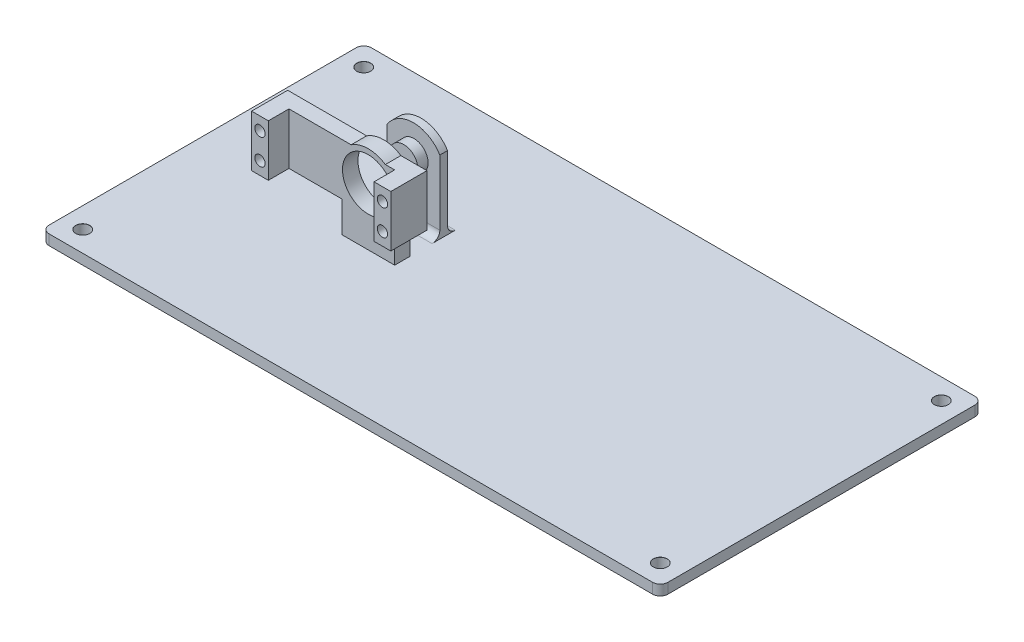
SolidWorks part; units mm, degrees
ref_plane "前视基准面" through (0, 0, 0) normal (0, 0, 1) x (1, 0, 0)
ref_plane "上视基准面" through (0, 0, 0) normal (0, 1, 0) x (1, 0, 0)
ref_plane "右视基准面" through (0, 0, 0) normal (1, 0, 0) x (0, 0, -1)
other "Configuration Table"
sketch "草图1" plane through (0, 0, 0) normal (0, 1, 0) x (1, 0, 0)
  line L1 (-120, -62.5) -> (120, -62.5)
  line L2 (-120, -62.5) -> (-120, 62.5)
  line L3 (-120, 62.5) -> (120, 62.5)
  line L4 (120, -62.5) -> (120, 62.5)
  line L5 (-120, -62.5) -> (120, 62.5) construction
  line L6 (-120, 62.5) -> (120, -62.5) construction
  point P0 (0, 0)
  dimension "D1" = 240
  dimension "D2" = 125
extrude "凸台-拉伸1" add sketch "草图1" along normal blind 4
sketch "草图2" plane through (0, 4, 0) normal (0, 1, 0) x (1, 0, 0)
  line L0 (-120, 0) -> (120, 0) construction
  line L1 (-120, 62.5) -> (-120, -62.5) construction
  line L2 (120, -62.5) -> (120, 62.5) construction
  line L3 (0, 62.5) -> (0, -62.5) construction
  line L4 (120, 62.5) -> (-120, 62.5) construction
  line L5 (-120, -62.5) -> (120, -62.5) construction
  point P12 (-112, 54.5)
  point P13 (-112, -54.5)
  point P14 (112, -54.5)
  point P15 (112, 54.5)
  dimension "D1" = 8
  dimension "D2" = 8
hole_wizard "Ø5.4 (5.4) 直径孔1" positions "草图2" profile "草图3" hole size "Ø5.4" standard "GB" end condition through all
sketch "草图3" plane through (112, 4, -54.5) normal (1, 0, 0) x (0, 0, 1)
  line L0 (0, 0) -> (0, 4)
  line L1 (0, 4) -> (2.7, 4)
  line L2 (2.7, 4) -> (2.7, 0.025)
  line L3 (2.7, 0.025) -> (2.725, 0)
  line L5 (2.725, 0) -> (0, 0)
  line L6 (-2.7, 0.025) -> (-2.725, 0) construction
  line L11 (0, -6.35) -> (0, 107.95) construction
  dimension "通孔孔直径" = 5.4
  dimension "通孔孔深度" = 4
  dimension "近端锥形沉头孔直径" = 5.45
  dimension "近端锥形沉头孔角度" = 90
fillet "圆角1" radius 3 4 edges at (120, 2, 62.5) (120, 2, -62.5) (-120, 2, 62.5) (-120, 2, -62.5)
sketch "草图5" plane through (0, 0, 0) normal (0, 0, 1) x (1, 0, 0)
  line L0 (0, 0) -> (0, 4) construction
  line L1 (-117, 4) -> (117, 4) construction
  line L2 (-60, 0) -> (-60, 4) construction
  line L3 (-117, 0) -> (117, 0) construction
  line L4 (-60, 4) -> (-39.5, 4)
  line L5 (-33, 16) -> (-33, 36)
  line L6 (-33, 36) -> (-43.1168, 36)
  line L8 (-87, 16) -> (-87, 36)
  line L9 (-60, 4) -> (-60, 36) construction
  line L10 (-60, 16) -> (-87, 16)
  line L12 (-49.75, 4) -> (-49.75, 14) construction
  line L13 (-33, 16) -> (-39.5, 16)
  line L14 (-33, 26) -> (-87, 26) construction
  line L15 (-39.5, 16) -> (-39.5, 4)
  line L16 (-49.75, 16) -> (-49.75, 36) construction
  line L17 (-56.3832, 36) -> (-87, 36)
  line L18 (-60, 16) -> (-60, 4)
  arc A1 (-43.1168, 36) -> (-56.3832, 36) centre (-49.75, 26) ccw
  circle A2 centre (-49.75, 26) radius 10
  point P13 (-60, 36)
  dimension "D1" = 60
  dimension "D5" = 20
extrude "凸台-拉伸2" add sketch "草图5" along normal blind 6
sketch "草图6" plane through (0, 0, 0) normal (0, 0, -1) x (-1, 0, 0)
  line L0 (39.5, 4) -> (60, 4)
  line L5 (60, 4) -> (60, 32.24)
  line L9 (39.5, 32.24) -> (39.5, 4)
  line L10 (39.5, 16) -> (60, 16) construction
  line L11 (49.75, 16) -> (49.75, 36) construction
  line L12 (49.75, 26) -> (39.5, 26) construction
  line L13 (39.5, 26) -> (60, 26) construction
  arc A1 (60, 32.24) -> (39.5, 32.24) centre (49.75, 26) ccw
  arc A2 (56.3832, 36) -> (43.1168, 36) centre (49.75, 26) ccw construction
  point P5 (39.5, 32.24)
  point P21 (43.1168, 36)
  point P22 (56.3832, 36)
  point P24 (60, 32.24)
extrude "凸台-拉伸3" add sketch "草图6" along normal blind 3 from offset 11.5
fillet "圆角2" radius 3 2 edges at (-49.75, 4, -14.5) (-49.75, 4, -11.5)
sketch "草图8" plane through (0, 0, 6) normal (0, 0, 1) x (1, 0, 0)
  line L0 (-33, 16) -> (-39.5, 16)
  line L1 (-39.5, 16) -> (-39.5, 36)
  line L2 (-33, 36) -> (-43.1168, 36) construction
  line L3 (-39.5, 36) -> (-33, 36)
  line L4 (-33, 36) -> (-33, 16)
  line L5 (-87, 36) -> (-87, 16)
  line L6 (-87, 16) -> (-80.5, 16)
  line L7 (-87, 16) -> (-60, 16) construction
  line L8 (-80.5, 16) -> (-80.5, 36)
  line L9 (-56.3832, 36) -> (-87, 36) construction
  line L10 (-80.5, 36) -> (-87, 36)
  dimension "D1" = 6.5
extrude "凸台-拉伸4" add sketch "草图8" along normal blind 8
sketch "草图10" plane through (0, 0, 14) normal (0, 0, 1) x (1, 0, 0)
  line L0 (-87, 26) -> (-80.5, 26) construction
  line L1 (-87, 36) -> (-87, 16) construction
  line L2 (-80.5, 16) -> (-80.5, 36) construction
  line L3 (-83.75, 36) -> (-83.75, 16) construction
  line L4 (-80.5, 36) -> (-87, 36) construction
  line L5 (-87, 16) -> (-80.5, 16) construction
  line L6 (-60, 16) -> (-60, 36) construction
  line L7 (-56.3832, 36) -> (-80.5, 36) construction
  circle A0 centre (-83.75, 31) radius 2
  circle A1 centre (-83.75, 21) radius 2
  circle A2 centre (-36.25, 21) radius 2
  circle A3 centre (-36.25, 31) radius 2
  dimension "D1" = 4
  dimension "D2" = 5
extrude "切除-拉伸1" cut sketch "草图10" against normal through all
sketch "草图11" plane through (0, 0, -14.5) normal (0, 0, -1) x (-1, 0, 0)
  circle A0 centre (49.5018, 27.3029) radius 5.4867
  dimension "D1" = 10.9733
extrude "凸台-拉伸5" add sketch "草图11" against normal blind 7
